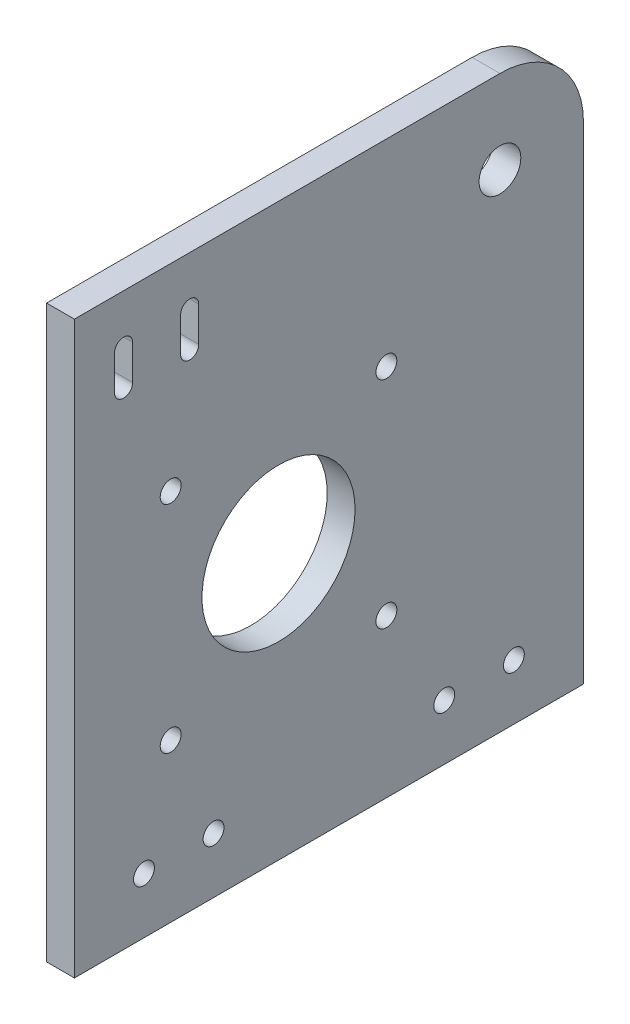
SolidWorks part; units mm, degrees
ref_plane "前视基准面" through (0, 0, 0) normal (0, 0, 1) x (1, 0, 0)
ref_plane "上视基准面" through (0, 0, 0) normal (0, 1, 0) x (1, 0, 0)
ref_plane "右视基准面" through (0, 0, 0) normal (1, 0, 0) x (0, 0, -1)
sketch "草图1" plane through (0, 0, 0) normal (1, 0, 0) x (0, 0, -1)
  line L0 (0, 0) -> (-49.1551, 34.406) construction
  line L1 (0, 0) -> (-49.1551, 0) construction
  line L2 (-49.1551, 34.406) -> (-49.1551, 0) construction
  line L3 (-61.1551, -70) -> (-61.1551, 12)
  line L4 (12, 0) -> (12, -70)
  line L5 (-61.1551, 12) -> (0, 12)
  line L6 (-61.1551, -70) -> (12, -70)
  line L7 (0, 0) -> (-31.8198, -31.8198) construction
  line L8 (12, -70) -> (12, -62)
  line L9 (12, -62) -> (2, -62) construction
  line L10 (2, -62) -> (-8, -62) construction
  line L11 (-61.1551, -70) -> (-61.1551, -62)
  line L12 (-61.1551, -62) -> (-51.1551, -62) construction
  line L13 (-51.1551, -62) -> (-41.1551, -62) construction
  line L14 (-31.8198, -31.8198) -> (-16.3198, -31.8198) construction
  line L15 (-16.3198, -31.8198) -> (-16.3198, -16.3198) construction
  circle A0 centre (0, 0) radius 3
  arc A1 (6.8812, 9.831) -> (0, 12) centre (0, 0) ccw
  circle A2 centre (-51.1551, -62) radius 1.5
  arc A3 (6.8812, 9.831) -> (12, 0) centre (0, 0) cw
  circle A4 centre (-31.8198, -31.8198) radius 11
  circle A5 centre (-41.1551, -62) radius 1.5
  circle A6 centre (-8, -62) radius 1.5
  circle A7 centre (2, -62) radius 1.5
  circle A8 centre (-16.3198, -16.3198) radius 1.5
  circle A9 centre (-16.3198, -47.3198) radius 1.5
  circle A10 centre (-47.3198, -47.3198) radius 1.5
  circle A11 centre (-47.3198, -16.3198) radius 1.5
  point P34 (-31.8198, -31.8198)
  dimension "D3" = 8
  dimension "D4" = 10
  dimension "D5" = 70
  dimension "D7" = 10
  dimension "D10" = 22
  dimension "D13" = 4
  dimension "D1" = 60
  dimension "D2" = 34.406
  dimension "D6" = 45
  dimension "D8" = 10
  dimension "D9" = 10
  dimension "D11" = 15.5
  dimension "D12" = 15.5
extrude "凸台-拉伸1" add sketch "草图1" along normal blind 4
sketch "草图2" plane through (4, 0, 0) normal (1, 0, 0) x (0, 0, -1)
  line L0 (-61.1551, 12) -> (-54.0841, 4.9289) construction
  line L1 (-54.0841, 4.9289) -> (-44.5841, 4.9289) construction
  line L2 (-55.3841, 4.9289) -> (-55.3841, -0.0711)
  line L3 (-55.3841, -0.0711) -> (-52.7841, -0.0711) construction
  line L4 (-52.7841, -0.0711) -> (-52.7841, 4.9289)
  line L5 (-45.8841, 4.9289) -> (-45.8841, -0.0711)
  line L6 (-45.8841, -0.0711) -> (-43.2841, -0.0711) construction
  line L7 (-43.2841, -0.0711) -> (-43.2841, 4.9289)
  arc A0 (-55.3841, 4.9289) -> (-52.7841, 4.9289) centre (-54.0841, 4.9289) cw
  arc A1 (-55.3841, -0.0711) -> (-52.7841, -0.0711) centre (-54.0841, -0.0711) ccw
  arc A2 (-45.8841, 4.9289) -> (-43.2841, 4.9289) centre (-44.5841, 4.9289) cw
  arc A3 (-45.8841, -0.0711) -> (-43.2841, -0.0711) centre (-44.5841, -0.0711) ccw
  dimension "D1" = 9.5
  dimension "D2" = 5
extrude "切除-拉伸1" cut sketch "草图2" against normal blind 10 contours L2 A1 L4 A0 | L5 A3 L7 A2
